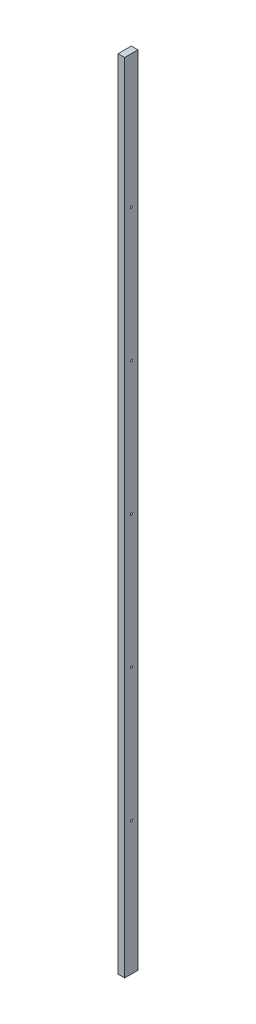
SolidWorks part; units mm, degrees
ref_plane "Спереди" through (0, 0, 0) normal (0, 0, 1) x (1, 0, 0)
ref_plane "Сверху" through (0, 0, 0) normal (0, 1, 0) x (1, 0, 0)
ref_plane "Справа" through (0, 0, 0) normal (1, 0, 0) x (0, 0, -1)
other "Configuration Table"
sketch "Эскиз1" plane through (0, 0, 0) normal (0, 1, 0) x (1, 0, 0)
  line L1 (12.5, 25) -> (-12.5, 25)
  line L2 (12.5, 25) -> (12.5, -25)
  line L3 (12.5, -25) -> (-12.5, -25)
  line L4 (-12.5, 25) -> (-12.5, -25)
  line L5 (12.5, 25) -> (-12.5, -25) construction
  line L6 (12.5, -25) -> (-12.5, 25) construction
  point P0 (0, 0)
extrude "Бобышка-Вытянуть1" add sketch "Эскиз1" along normal blind 3000
sketch "Эскиз2" plane through (12.5, 0, 0) normal (1, 0, 0) x (0, 0, -1)
  line L0 (0, 0) -> (0, 500) construction
  line L1 (-25, 0) -> (25, 0) construction
  line L2 (0, 500) -> (0, 1000) construction
  line L3 (0, 1000) -> (0, 1500) construction
  line L4 (0, 1500) -> (0, 2000) construction
  line L5 (0, 2000) -> (0, 2500) construction
  circle A0 centre (0, 2500) radius 4
  circle A1 centre (0, 2000) radius 4
  circle A2 centre (0, 1500) radius 4
  circle A3 centre (0, 1000) radius 4
  circle A4 centre (0, 500) radius 4
extrude "Вырез-Вытянуть1" cut sketch "Эскиз2" against normal blind 3000
